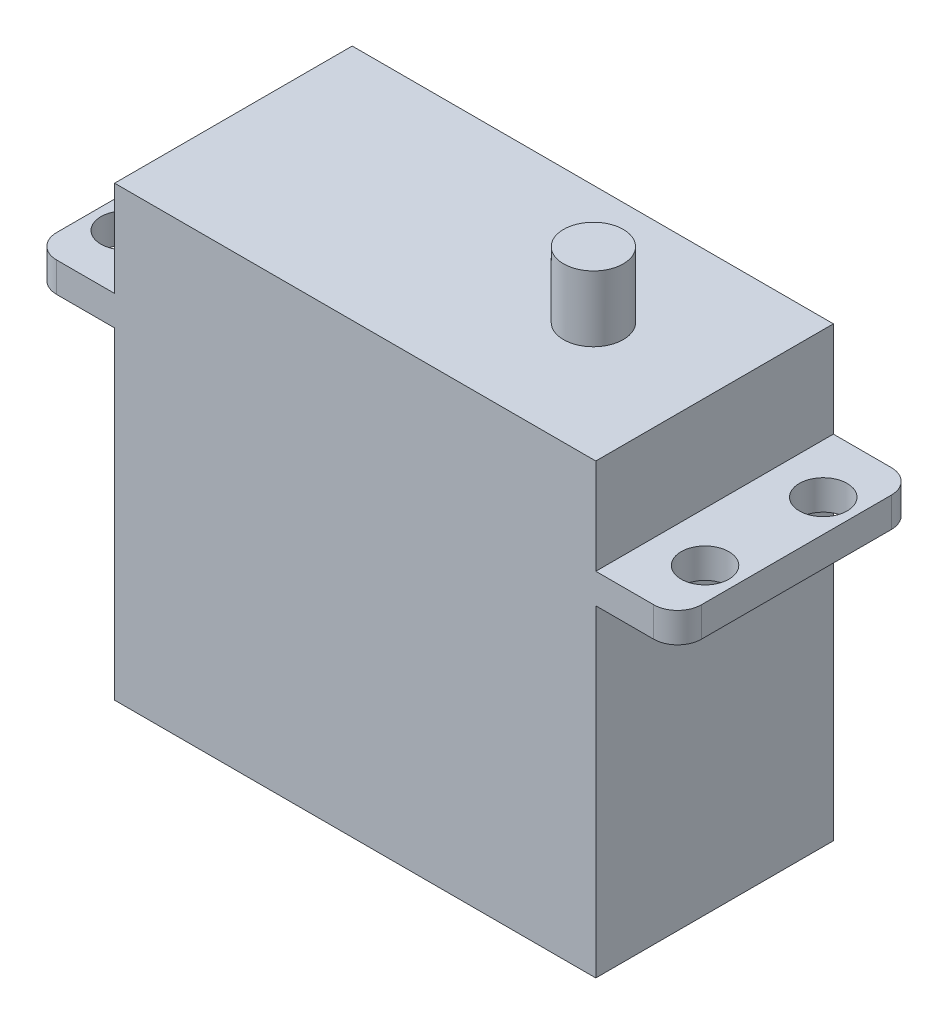
SolidWorks part; units mm, degrees
ref_plane "前视基准面" through (0, 0, 0) normal (0, 0, 1) x (1, 0, 0)
ref_plane "上视基准面" through (0, 0, 0) normal (0, 1, 0) x (1, 0, 0)
ref_plane "右视基准面" through (0, 0, 0) normal (1, 0, 0) x (0, 0, -1)
sketch "草图4" plane through (0, 0, 0) normal (0, 1, 0) x (1, 0, 0)
  line L1 (-20.15, -9.95) -> (20.15, -9.95)
  line L2 (-20.15, -9.95) -> (-20.15, 9.95)
  line L3 (-20.15, 9.95) -> (20.15, 9.95)
  line L4 (20.15, -9.95) -> (20.15, 9.95)
  line L5 (0, 9.95) -> (0, -9.95) construction
  line L6 (-20.15, 0) -> (20.15, 0) construction
  point P0 (0, 0)
  dimension "D1" = 40.3
  dimension "D2" = 19.9
extrude "凸台-拉伸2" add sketch "草图4" along normal blind 37.5
sketch "草图5" plane through (0, 0, 0) normal (0, 1, 0) x (1, 0, 0)
  line L0 (20.15, 9.95) -> (-20.15, 9.95) construction
  line L1 (-27, -9.95) -> (27, -9.95)
  line L3 (-27, 9.95) -> (27, 9.95)
  line L5 (0, 9.95) -> (0, -9.95) construction
  line L6 (-31.9852, 0) -> (31.2776, 0) construction
  line L9 (27, -9.95) -> (27, 9.95)
  line L12 (-27, -9.95) -> (-27, 9.95)
  circle A2 centre (24.3, 4.95) radius 2
  circle A3 centre (24.3, -4.95) radius 2
  circle A4 centre (-24.3, -4.95) radius 2
  circle A5 centre (-24.3, 4.95) radius 2
  point P0 (0, 0)
  dimension "D3" = 9.9
  dimension "D2" = 4
  dimension "D1" = 54
  dimension "D4" = 48.6
extrude "凸台-拉伸3" add sketch "草图5" along normal blind 2.5 from offset 27
ref_plane "基准面4" through (0, 37.5, 0) normal (0, 1, 0) x (1, 0, 0)
sketch "草图6" plane through (0, 37.5, 0) normal (0, 1, 0) x (1, 0, 0)
  line L0 (-21.6478, 0) -> (23.0654, 0) construction
  circle A0 centre (10, 0) radius 2.5
  circle A1 centre (-24.3, 4.95) radius 2 construction
  circle A2 centre (-24.3, 4.95) radius 2 construction
  dimension "D1" = 5
  dimension "D2" = 34.3
extrude "凸台-拉伸4" add sketch "草图6" along normal blind 5.5
ref_plane "基准面5" through (0, 32.9, 0) normal (0, -1, 0) x (-1, 0, 0)
sketch "草图8" plane through (0, 32.9, 0) normal (0, -1, 0) x (-1, 0, 0)
  circle A0 centre (-10, 0) radius 2.25
  circle A1 centre (-10, 0) radius 2.5 construction
  dimension "D1" = 4.5
extrude "凸台-拉伸5" add sketch "草图8" along normal up to next (32.9 mm away) from offset 2.37
fillet "圆角1" radius 2 4 edges at (27, 28.25, -9.95) (27, 28.25, 9.95) (-27, 28.25, -9.95) (-27, 28.25, 9.95)
equation "\"4、\"=5"
